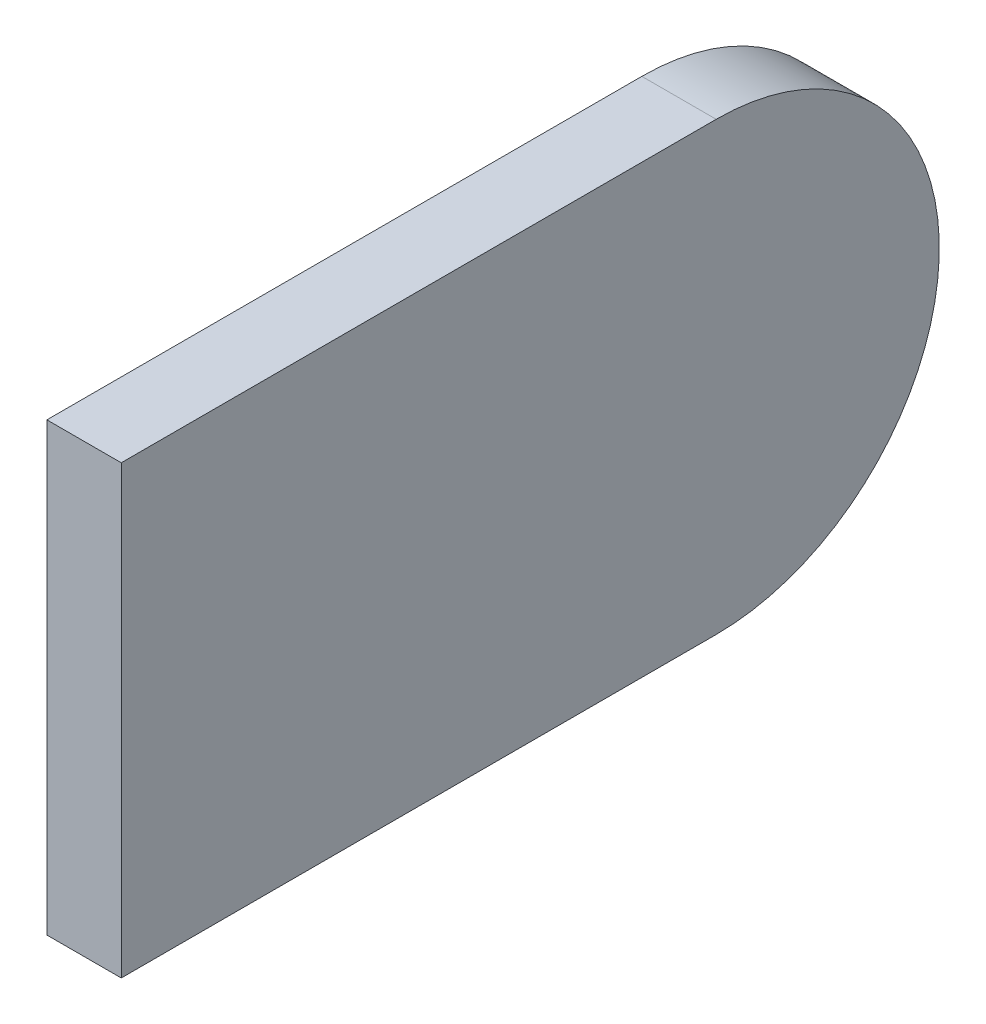
SolidWorks part; units mm, degrees
material "Plain Carbon Steel"
ref_plane "Front Plane" through (0, 0, 0) normal (0, 0, 1) x (1, 0, 0)
ref_plane "Top Plane" through (0, 0, 0) normal (0, 1, 0) x (1, 0, 0)
ref_plane "Right Plane" through (0, 0, 0) normal (1, 0, 0) x (0, 0, -1)
sketch "Sketch2" plane through (0, 0, 0) normal (1, 0, 0) x (0, 0, -1)
  line L0 (0, 0) -> (80, 0)
  line L1 (0, 0) -> (0, 60)
  line L2 (0, 60) -> (80, 60)
  arc A0 (80, 60) -> (80, 0) centre (80, 30) cw
  dimension "D2" = 30
  dimension "D1" = 80
extrude "Boss-Extrude1" add sketch "Sketch2" along normal blind 10
